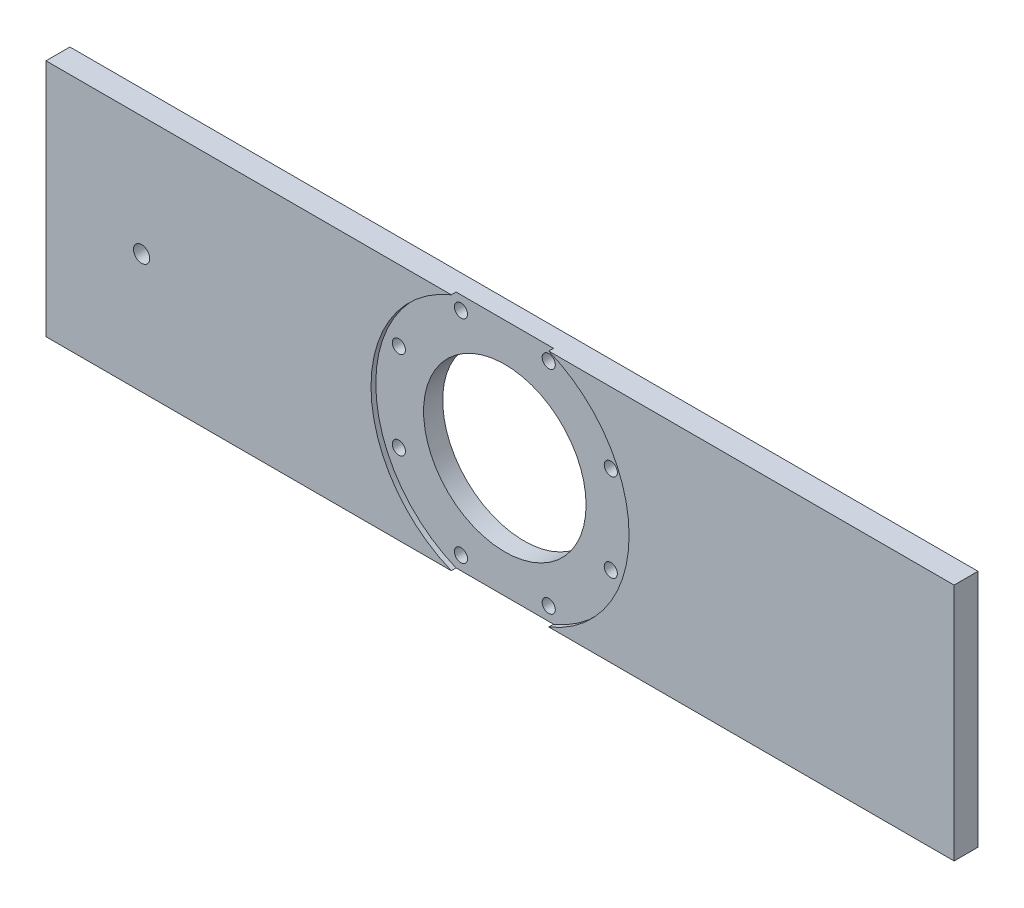
SolidWorks part; units mm, degrees
ref_plane "Piano frontale" through (0, 0, 0) normal (0, 0, 1) x (1, 0, 0)
ref_plane "Piano superiore" through (0, 0, 0) normal (0, 1, 0) x (1, 0, 0)
ref_plane "Piano destro" through (0, 0, 0) normal (1, 0, 0) x (0, 0, -1)
sketch "Schizzo1" plane through (0, 0, 0) normal (0, 0, 1) x (1, 0, 0)
  line L1 (190, -50) -> (-190, -50)
  line L2 (190, -50) -> (190, 50)
  line L3 (190, 50) -> (-190, 50)
  line L4 (-190, -50) -> (-190, 50)
  line L5 (190, -50) -> (-190, 50) construction
  line L6 (190, 50) -> (-190, -50) construction
  point P0 (0, 0)
  dimension "D1" = 100
  dimension "D2" = 380
extrude "Estrusione-Estrusione1" add sketch "Schizzo1" along normal blind 10 contours L3 L4 L1 L2
sketch "Schizzo2" plane through (0, 0, 10) normal (0, 0, 1) x (1, 0, 0)
  circle A0 centre (0, 0) radius 54
  dimension "D1" = 108
extrude "Taglio-Estrusione1" cut sketch "Schizzo2" against normal blind 2
sketch "Schizzo3" plane through (0, 0, 8) normal (0, 0, 1) x (1, 0, 0)
  line L0 (0, 0) -> (-48, 0) construction
  line L1 (0, 0) -> (-44.3462, -18.3688) construction
  circle A0 centre (0, 0) radius 48 construction
  circle A1 centre (-44.3462, -18.3688) radius 2.75
  dimension "D1" = 96
  dimension "D2" = 5.5
  dimension "D3" = 22.5
extrude "Taglio-Estrusione2" cut sketch "Schizzo3" against normal through all
pattern_circular "RipetizioneCircolare1" count 8 over 360 about axis through (0, 0, 0) along (0, 0, 1) of "Taglio-Estrusione2"
sketch "Schizzo4" plane through (0, 0, 8) normal (0, 0, 1) x (1, 0, 0)
  circle A0 centre (0, 0) radius 34
  dimension "D1" = 68
extrude "Taglio-Estrusione3" cut sketch "Schizzo4" against normal through all
sketch "Schizzo5" plane through (0, 0, 10) normal (0, 0, 1) x (1, 0, 0)
  line L0 (0, 0) -> (-150, 0) construction
  circle A0 centre (-150, 0) radius 3.4
  dimension "D2" = 6.8
  dimension "D1" = 150
extrude "Taglio-Estrusione4" cut sketch "Schizzo5" against normal through all
